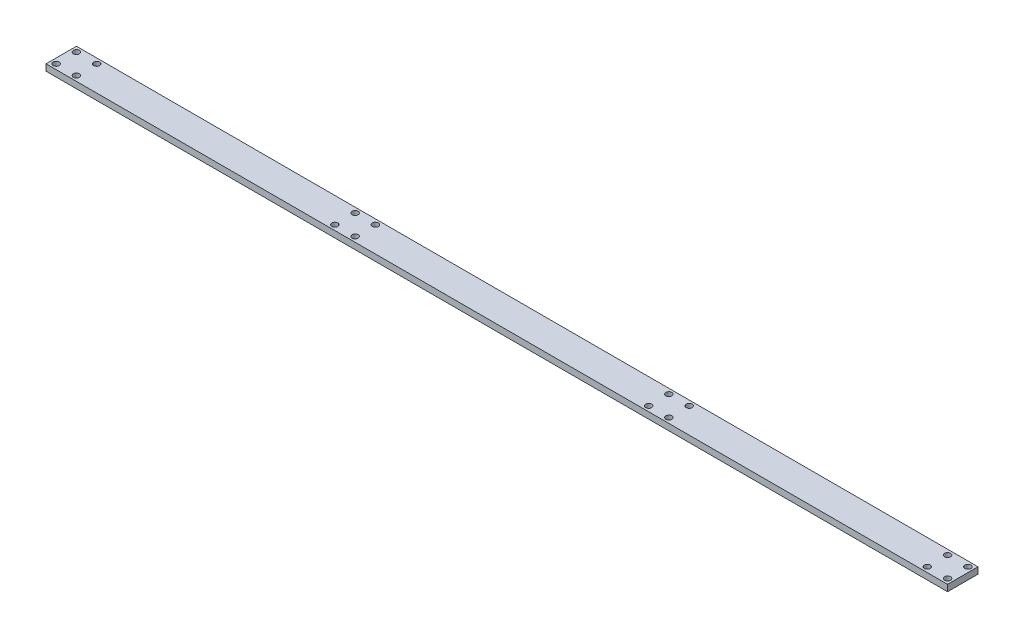
SolidWorks part; units mm, degrees
ref_plane "Front Plane" through (0, 0, 0) normal (0, 0, 1) x (1, 0, 0)
ref_plane "Top Plane" through (0, 0, 0) normal (0, 1, 0) x (1, 0, 0)
ref_plane "Right Plane" through (0, 0, 0) normal (1, 0, 0) x (0, 0, -1)
sketch "Sketch1" plane through (0, 0, 0) normal (0, 1, 0) x (1, 0, 0)
  line L0 (152.4, 7.5) -> (144.9, 7.5)
  line L1 (0, 0) -> (152.4, 0)
  line L2 (0, 0) -> (0, 15)
  line L3 (0, 15) -> (152.4, 15)
  line L4 (152.4, 0) -> (152.4, 15)
  line L5 (0, 7.5) -> (7.5, 7.5)
  line L6 (7.5, 7.5) -> (7.5, 12.5)
  line L7 (7.5, 12.5) -> (2.5, 12.5)
  line L8 (7.5, 12.5) -> (12.5, 12.5)
  line L9 (7.5, 7.5) -> (7.5, 2.5)
  line L10 (7.5, 2.5) -> (2.5, 2.5)
  line L11 (7.5, 2.5) -> (12.5, 2.5)
  line L12 (76.2, 0) -> (76.2, 15)
  line L13 (152.4, 0) -> (152.4, 15)
  line L14 (152.4, 0) -> (292.1, 0)
  line L15 (152.4, 15) -> (292.1, 15)
  line L16 (222.25, 0) -> (222.25, 15)
  line L17 (292.1, 0) -> (292.1, 15)
  line L18 (444.5, 15) -> (292.1, 15)
  line L19 (292.1, 0) -> (292.1, 15)
  line L20 (444.5, 0) -> (292.1, 0)
  line L21 (444.5, 0) -> (444.5, 15)
  circle A0 centre (2.5, 2.5) radius 1.5
  circle A1 centre (2.5, 12.5) radius 1.5
  circle A2 centre (12.5, 12.5) radius 1.5
  circle A3 centre (12.5, 2.5) radius 1.5
  circle A4 centre (149.9, 12.5) radius 1.5
  circle A5 centre (139.9, 12.5) radius 1.5
  circle A6 centre (149.9, 2.5) radius 1.5
  circle A7 centre (139.9, 2.5) radius 1.5
  circle A8 centre (432, 12.5) radius 1.5
  circle A9 centre (442, 12.5) radius 1.5
  circle A10 centre (442, 2.5) radius 1.5
  circle A11 centre (432, 2.5) radius 1.5
  circle A12 centre (294.6, 12.5) radius 1.5
  circle A13 centre (304.6, 12.5) radius 1.5
  circle A14 centre (304.6, 2.5) radius 1.5
  circle A15 centre (294.6, 2.5) radius 1.5
  dimension "D11" = 69.85
  dimension "D1" = 15
  dimension "D2" = 152.4
  dimension "D3" = 7.5
  dimension "D4" = 7.5
  dimension "D5" = 5
  dimension "D6" = 5
  dimension "D7" = 5
  dimension "D8" = 5
  dimension "D9" = 5
  dimension "D10" = 5
extrude "Boss-Extrude1" add sketch "Sketch1" along normal blind 3.175
